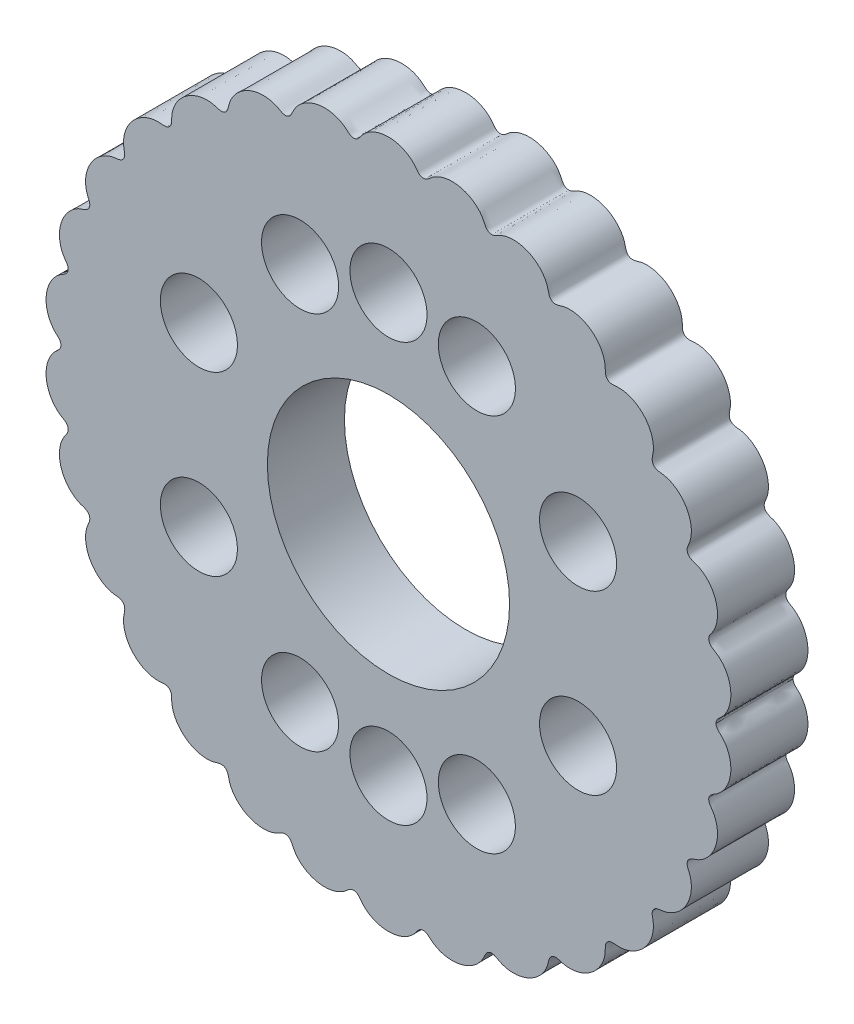
SolidWorks part; units mm, degrees
ref_plane "Plan de face" through (0, 0, 0) normal (0, 0, 1) x (1, 0, 0)
ref_plane "Plan de dessus" through (0, 0, 0) normal (0, 1, 0) x (1, 0, 0)
ref_plane "Plan de droite" through (0, 0, 0) normal (1, 0, 0) x (0, 0, -1)
sketch "Esquisse1" plane through (0, 0, 0) normal (0, 0, 1) x (1, 0, 0)
  line L0 (-1000, 0) -> (49000, 0) construction
  spline S0 degree 4 poles (29.8631, 8.2305) (29.8499, 8.1217) (29.8133, 7.9053) (29.7416, 7.64) (29.6157, 7.3353) (29.4839, 7.095) (29.3642, 6.911) (29.2467, 6.7537) (29.1538, 6.6056) (29.0902, 6.432) (29.0737, 6.2397) (29.1354, 6.023) (29.2904, 5.838) (29.4774, 5.7198) (29.6579, 5.6163) (29.8231, 5.5082) (30.0196, 5.3594) (30.2372, 5.1583) (30.5232, 4.8242) (30.8216, 4.3213) (31.0469, 3.679) (31.1337, 2.9091) (31.0567, 2.2277) (30.8902, 1.7108) (30.7109, 1.353) (30.5728, 1.1334) (30.4496, 0.9663) (30.3139, 0.8094) (30.1671, 0.6626) (30.0393, 0.549) (29.9425, 0.4546) (29.8803, 0.3777) (29.8449, 0.3262) (29.8141, 0.2716) (29.7888, 0.2141) (29.7717, 0.1632) (29.761, 0.1169) (29.7536, 0.0672) (29.7495, 0.017) (29.7494, -0.0206) (29.7556, -0.0898) (29.7678, -0.1499) (29.7904, -0.2203) (29.8284, -0.303) (29.8828, -0.3847) (29.9529, -0.4642) (30.04, -0.5488) (30.1416, -0.6407) (30.2572, -0.7512) (30.3813, -0.8854) (30.4962, -1.0277) (30.6276, -1.2147) (30.7721, -1.4641) (30.9126, -1.7829) (31.0276, -2.1744) (31.0935, -2.591) (31.107, -3.0187) (31.0662, -3.4508) (30.9693, -3.8803) (30.8145, -4.2991) (30.6117, -4.6792) (30.3965, -4.9766) (30.1917, -5.1998) (30.0146, -5.3603) (29.8643, -5.4786) (29.7061, -5.5858) (29.542, -5.684) (29.3671, -5.785) (29.2042, -5.9269) (29.0936, -6.1295) (29.0703, -6.371) (29.1391, -6.5914) (29.2598, -6.7697) (29.3791, -6.934) (29.4834, -7.0955) (29.5997, -7.3056) (29.715, -7.5703) (29.8147, -7.8969) (29.8798, -8.2857) (29.896, -8.684) (29.8631, -9.0858) (29.7829, -9.4799) (29.6574, -9.8612) (29.4885, -10.2243) (29.2783, -10.5643) (29.0303, -10.8742) (28.7824, -11.1148) (28.5506, -11.2952) (28.3468, -11.4258) (28.1768, -11.5188) (28.0006, -11.599) (27.8193, -11.6676) (27.6244, -11.7296) (27.4217, -11.8089) (27.242, -11.9571) (27.1301, -12.1734) (27.113, -12.404) (27.1707, -12.6114) (27.2542, -12.795) (27.3276, -12.9715) (27.3906, -13.1518) (27.4404, -13.3363) (27.4866, -13.5706) (27.5177, -13.8717) (27.5133, -14.2384) (27.4499, -14.6642) (27.3252, -15.0926) (27.1465, -15.4978) (26.919, -15.8739) (26.6474, -16.2153) (26.3365, -16.5168) (26.0024, -16.764) (25.654, -16.9563) (25.3418, -17.0779) (25.0791, -17.148) (24.8562, -17.1866) (24.6765, -17.2082) (24.4854, -17.2287) (24.2872, -17.2853) (24.1038, -17.4139) (23.9758, -17.6159) (23.9376, -17.8434) (23.9703, -18.0586) (24.0141, -18.2584) (24.0453, -18.4498) (24.0639, -18.6424) (24.0684, -18.8361) (24.0572, -19.0779) (24.0169, -19.3689) (23.9324, -19.7039) (23.7881, -20.0736) (23.5988, -20.4256) (23.3687, -20.7534) (23.1013, -21.0528) (22.8001, -21.3193) (22.4685, -21.5487) (22.1155, -21.7338) (21.7463, -21.8718) (21.4135, -21.9488) (21.1267, -21.9813) (20.8866, -21.9856) (20.6945, -21.9761) (20.4927, -21.9549) (20.2778, -21.9395) (20.0526, -21.9901) (19.8551, -22.131) (19.7349, -22.3281) (19.6935, -22.5401) (19.6935, -22.7421) (19.6905, -22.9333) (19.6768, -23.124) (19.6495, -23.3133) (19.599, -23.5469) (19.5081, -23.8358) (19.3582, -24.1709) (19.1304, -24.5365) (18.8451, -24.88) (18.5216, -25.1787) (18.1677, -25.4301) (17.7906, -25.6322) (17.3968, -25.7835) (17.0003, -25.8796) (16.6085, -25.9224) (16.2742, -25.9148) (16.002, -25.8785) (15.7793, -25.8278) (15.6036, -25.7769) (15.4169, -25.7147) (15.2087, -25.6689) (14.9779, -25.6954) (14.7639, -25.8189) (14.6256, -26.0056) (14.5611, -26.2088) (14.5217, -26.4015) (14.4779, -26.5791) (14.4104, -26.7974) (14.3058, -27.0513) (14.1452, -27.3445) (13.9122, -27.6625) (13.6308, -27.9579) (13.3029, -28.2232) (12.9393, -28.4488) (12.5446, -28.6295) (12.1242, -28.7604) (11.6841, -28.8357) (11.2535, -28.8501) (10.8884, -28.8124) (10.5927, -28.7466) (10.3651, -28.6736) (10.1875, -28.6026) (10.0156, -28.5191) (9.8485, -28.4261) (9.6736, -28.3252) (9.4693, -28.255) (9.2385, -28.2605) (9.0177, -28.3611) (8.8612, -28.5309) (8.7671, -28.7246) (8.6846, -28.91) (8.5968, -29.0812) (8.473, -29.2869) (8.3014, -29.519) (8.0684, -29.7687) (7.7643, -30.0195) (7.4274, -30.2327) (7.0631, -30.4051) (6.6816, -30.5327) (6.2887, -30.6146) (5.8897, -30.6499) (5.4902, -30.6379) (5.0979, -30.5781) (4.7655, -30.4837) (4.4934, -30.3731) (4.2784, -30.2619) (4.1128, -30.1612) (3.9553, -30.0487) (3.8052, -29.926) (3.6541, -29.7882) (3.484, -29.6523) (3.2679, -29.5716) (3.029, -29.5815) (2.8259, -29.676) (2.6778, -29.8193) (2.5645, -29.9746) (2.456, -30.1194) (2.311, -30.2931) (2.119, -30.4856) (1.8576, -30.6952) (1.5168, -30.9007) (1.1357, -31.0665) (0.7192, -31.185) (0.2877, -31.2495) (-0.1517, -31.2585) (-0.592, -31.2106) (-1.0254, -31.1045) (-1.4258, -30.9464) (-1.7456, -30.7669) (-1.9908, -30.5894) (-2.1706, -30.4322) (-2.3055, -30.2968) (-2.4301, -30.1521) (-2.5463, -30.0003) (-2.6635, -29.8363) (-2.8143, -29.6826) (-3.0226, -29.582) (-3.2659, -29.5708) (-3.484, -29.6523) (-3.654, -29.7882) (-3.8052, -29.926) (-3.9553, -30.0487) (-4.1128, -30.1612) (-4.2784, -30.2619) (-4.4934, -30.3731) (-4.7655, -30.4837) (-5.0979, -30.5781) (-5.4902, -30.6379) (-5.8897, -30.6499) (-6.2887, -30.6146) (-6.6816, -30.5327) (-7.0631, -30.4051) (-7.4274, -30.2327) (-7.7643, -30.0195) (-8.0684, -29.7687) (-8.3014, -29.519) (-8.473, -29.2869) (-8.5968, -29.0812) (-8.6846, -28.91) (-8.7671, -28.7246) (-8.8612, -28.5309) (-9.0177, -28.3611) (-9.2385, -28.2605) (-9.4693, -28.255) (-9.6736, -28.3252) (-9.8485, -28.4261) (-10.0156, -28.5191) (-10.1875, -28.6026) (-10.3651, -28.6736) (-10.5927, -28.7466) (-10.8884, -28.8124) (-11.2535, -28.8501) (-11.6841, -28.8357) (-12.1242, -28.7604) (-12.5446, -28.6295) (-12.9393, -28.4488) (-13.3029, -28.2232) (-13.6308, -27.9579) (-13.9122, -27.6625) (-14.1452, -27.3445) (-14.3058, -27.0513) (-14.4104, -26.7974) (-14.4779, -26.5791) (-14.5217, -26.4015) (-14.5611, -26.2088) (-14.6256, -26.0056) (-14.7639, -25.8189) (-14.9779, -25.6954) (-15.2087, -25.6689) (-15.4169, -25.7147) (-15.6036, -25.7769) (-15.7793, -25.8278) (-16.002, -25.8785) (-16.2742, -25.9148) (-16.6085, -25.9224) (-17.0003, -25.8796) (-17.3968, -25.7835) (-17.7906, -25.6322) (-18.1677, -25.4301) (-18.5216, -25.1787) (-18.8451, -24.88) (-19.1304, -24.5365) (-19.3582, -24.1709) (-19.5081, -23.8358) (-19.599, -23.5469) (-19.6495, -23.3133) (-19.6768, -23.124) (-19.6905, -22.9333) (-19.6935, -22.7421) (-19.6935, -22.5401) (-19.7349, -22.3281) (-19.8551, -22.131) (-20.0526, -21.9901) (-20.2778, -21.9395) (-20.4927, -21.9549) (-20.6945, -21.9761) (-20.8866, -21.9856) (-21.1267, -21.9813) (-21.4135, -21.9488) (-21.7463, -21.8718) (-22.1155, -21.7338) (-22.4685, -21.5487) (-22.8001, -21.3193) (-23.1013, -21.0528) (-23.3687, -20.7534) (-23.5988, -20.4256) (-23.7881, -20.0736) (-23.9324, -19.7039) (-24.0169, -19.3689) (-24.0572, -19.0779) (-24.0684, -18.8361) (-24.0639, -18.6424) (-24.0453, -18.4498) (-24.0141, -18.2584) (-23.9703, -18.0586) (-23.9376, -17.8434) (-23.9758, -17.6159) (-24.1038, -17.4139) (-24.2872, -17.2853) (-24.4854, -17.2287) (-24.6765, -17.2082) (-24.8562, -17.1866) (-25.0791, -17.148) (-25.3418, -17.0779) (-25.654, -16.9563) (-26.0024, -16.764) (-26.3365, -16.5168) (-26.6474, -16.2153) (-26.919, -15.8739) (-27.1465, -15.4978) (-27.3252, -15.0926) (-27.4499, -14.6642) (-27.5133, -14.2384) (-27.5177, -13.8717) (-27.4866, -13.5706) (-27.4404, -13.3363) (-27.3906, -13.1518) (-27.3276, -12.9715) (-27.2542, -12.795) (-27.1707, -12.6114) (-27.113, -12.404) (-27.1301, -12.1734) (-27.242, -11.9571) (-27.4217, -11.8089) (-27.6244, -11.7296) (-27.8193, -11.6676) (-28.0006, -11.599) (-28.1768, -11.5188) (-28.3468, -11.4258) (-28.5506, -11.2952) (-28.7824, -11.1148) (-29.0303, -10.8742) (-29.2783, -10.5643) (-29.4885, -10.2243) (-29.6574, -9.8612) (-29.7829, -9.4799) (-29.8631, -9.0858) (-29.896, -8.684) (-29.8798, -8.2857) (-29.8147, -7.8969) (-29.715, -7.5703) (-29.5997, -7.3056) (-29.4834, -7.0955) (-29.3791, -6.934) (-29.2598, -6.7697) (-29.1391, -6.5914) (-29.0703, -6.371) (-29.0936, -6.1295) (-29.2042, -5.9269) (-29.3671, -5.785) (-29.542, -5.684) (-29.7061, -5.5858) (-29.8643, -5.4786) (-30.0146, -5.3603) (-30.1917, -5.1998) (-30.3965, -4.9766) (-30.6117, -4.6792) (-30.8145, -4.2991) (-30.9693, -3.8803) (-31.0662, -3.4508) (-31.107, -3.0187) (-31.0935, -2.591) (-31.0276, -2.1744) (-30.9126, -1.7829) (-30.7537, -1.4222) (-30.58, -1.1364) (-30.4124, -0.919) (-30.2572, -0.7512) (-30.1416, -0.6407) (-30.04, -0.5488) (-29.9529, -0.4642) (-29.8828, -0.3847) (-29.8284, -0.303) (-29.7904, -0.2203) (-29.7678, -0.1499) (-29.7556, -0.0898) (-29.7494, -0.0206) (-29.7495, 0.0226) (-29.7561, 0.094) (-29.7693, 0.1557) (-29.7888, 0.2141) (-29.8141, 0.2716) (-29.8449, 0.3262) (-29.8803, 0.3778) (-29.9262, 0.4344) (-29.9834, 0.4947) (-30.0703, 0.5765) (-30.1854, 0.6811) (-30.3139, 0.8093) (-30.4835, 1.0056) (-30.6621, 1.2611) (-30.8291, 1.576) (-30.9678, 1.9517) (-31.0574, 2.3341) (-31.1011, 2.7166) (-31.1012, 3.1978) (-31.0148, 3.7704) (-30.8216, 4.3213) (-30.5232, 4.8242) (-30.2372, 5.1583) (-30.0196, 5.3594) (-29.8231, 5.5082) (-29.6579, 5.6163) (-29.4774, 5.7198) (-29.2904, 5.838) (-29.1354, 6.023) (-29.0737, 6.2397) (-29.0902, 6.432) (-29.1538, 6.6056) (-29.2467, 6.7537) (-29.3642, 6.911) (-29.4839, 7.095) (-29.6157, 7.3353) (-29.7416, 7.64) (-29.8133, 7.9053) (-29.8499, 8.1217) (-29.8631, 8.2305) knots 0 0 0 0 0 0.003392 0.006784 0.00848 0.010176 0.011872 0.013568 0.014566 0.015563 0.017559 0.01944 0.02132 0.022846 0.024371 0.025896 0.027421 0.030471 0.033522 0.039468 0.045414 0.051361 0.057307 0.060517 0.062121 0.063726 0.065331 0.066935 0.06854 0.070145 0.070628 0.071112 0.071596 0.07208 0.072564 0.073048 0.073289 0.073531 0.074015 0.07448 0.074945 0.07541 0.075875 0.076805 0.077735 0.078442 0.079149 0.080563 0.081977 0.083391 0.084805 0.086218 0.089046 0.092302 0.095557 0.098813 0.102069 0.105514 0.10896 0.112405 0.115851 0.118808 0.120287 0.121766 0.123244 0.124723 0.126202 0.12768 0.1295 0.131319 0.133154 0.134989 0.136475 0.137961 0.139448 0.140934 0.143906 0.146878 0.14999 0.153103 0.156215 0.159327 0.162414 0.1655 0.168586 0.171672 0.174668 0.176165 0.177663 0.179161 0.180659 0.182156 0.183654 0.185506 0.187357 0.189175 0.190994 0.192471 0.193949 0.195426 0.196904 0.198382 0.199859 0.202814 0.206257 0.2097 0.213143 0.216586 0.219928 0.22327 0.226613 0.229955 0.232755 0.235555 0.236955 0.238355 0.239755 0.241155 0.242909 0.244663 0.246515 0.248366 0.249864 0.251362 0.252859 0.254357 0.255855 0.257353 0.260348 0.263434 0.266521 0.269607 0.272693 0.275805 0.278918 0.28203 0.285143 0.288115 0.291087 0.292573 0.294059 0.295545 0.297031 0.298866 0.300701 0.302521 0.30434 0.305819 0.307297 0.308776 0.310255 0.311733 0.313212 0.31617 0.319615 0.323061 0.326506 0.329952 0.333207 0.336463 0.339719 0.342974 0.345802 0.34863 0.350043 0.351457 0.352871 0.354285 0.356145 0.358005 0.359865 0.361725 0.363139 0.364553 0.365967 0.367381 0.370208 0.373036 0.376292 0.379547 0.382803 0.386059 0.389504 0.39295 0.396395 0.399841 0.402798 0.404277 0.405755 0.407234 0.408713 0.410191 0.41167 0.41349 0.415309 0.417144 0.418979 0.420465 0.421951 0.423437 0.424923 0.427896 0.430868 0.43398 0.437092 0.440205 0.443317 0.446403 0.44949 0.452576 0.455662 0.458657 0.460155 0.461653 0.463151 0.464649 0.466146 0.467644 0.469495 0.471347 0.473101 0.474856 0.476256 0.477656 0.479056 0.480456 0.483256 0.486055 0.489398 0.49274 0.496082 0.499424 0.502867 0.50631 0.509753 0.513196 0.516151 0.517629 0.519106 0.520584 0.522061 0.523539 0.525016 0.526835 0.528653 0.530505 0.532356 0.533854 0.535351 0.536849 0.538347 0.539845 0.541343 0.544338 0.547424 0.55051 0.553597 0.556683 0.559795 0.562908 0.56602 0.569132 0.572104 0.575077 0.576563 0.578049 0.579535 0.581021 0.582856 0.584691 0.58651 0.58833 0.589809 0.591287 0.592766 0.594245 0.595723 0.597202 0.600159 0.603605 0.60705 0.610496 0.613941 0.617197 0.620453 0.623708 0.626964 0.629792 0.632619 0.634033 0.635447 0.636861 0.638275 0.640135 0.641995 0.643855 0.645715 0.647129 0.648543 0.649957 0.65137 0.654198 0.657026 0.660281 0.663537 0.666793 0.670048 0.673494 0.676939 0.680385 0.68383 0.686788 0.688267 0.689745 0.691224 0.692703 0.694181 0.69566 0.697479 0.699299 0.701134 0.702969 0.704455 0.705941 0.707427 0.708913 0.711885 0.714857 0.71797 0.721082 0.724195 0.727307 0.730393 0.733479 0.736566 0.739652 0.742647 0.744145 0.745643 0.747141 0.748638 0.750136 0.751634 0.753485 0.755337 0.757091 0.758845 0.760245 0.761645 0.763045 0.764445 0.767245 0.770045 0.773387 0.77673 0.780072 0.783414 0.786857 0.7903 0.793743 0.797186 0.800141 0.801618 0.803096 0.804574 0.806051 0.807529 0.809006 0.810825 0.812643 0.814494 0.816346 0.817844 0.819341 0.820839 0.822337 0.823835 0.825332 0.828328 0.831414 0.8345 0.837586 0.840673 0.843785 0.846897 0.85001 0.853122 0.856094 0.859066 0.860552 0.862039 0.863525 0.865011 0.866846 0.868681 0.8705 0.87232 0.873798 0.875277 0.876756 0.878234 0.879713 0.881192 0.884149 0.887595 0.89104 0.894486 0.897931 0.901187 0.904443 0.907698 0.910954 0.913782 0.916609 0.918023 0.919437 0.920851 0.921558 0.922265 0.923195 0.924125 0.92459 0.925055 0.92552 0.925985 0.926469 0.926952 0.927436 0.92792 0.928404 0.928888 0.929372 0.929855 0.930658 0.93146 0.933065 0.934669 0.936274 0.939483 0.942693 0.945666 0.948639 0.951612 0.954586 0.960532 0.966478 0.969529 0.972579 0.974104 0.975629 0.977154 0.97868 0.98056 0.982441 0.984437 0.985434 0.986432 0.988128 0.989824 0.99152 0.993216 0.996608 1 1 1 1 1 construction
  spline S1 degree 4 poles (29.75, 0) (29.75, -0.0128) (29.751, -0.0384) (29.7556, -0.0898) (29.7678, -0.1499) (29.7904, -0.2203) (29.8284, -0.303) (29.8828, -0.3847) (29.9529, -0.4642) (30.04, -0.5488) (30.1416, -0.6407) (30.2572, -0.7512) (30.3813, -0.8854) (30.4962, -1.0277) (30.6276, -1.2147) (30.7721, -1.4641) (30.9126, -1.7829) (31.0276, -2.1744) (31.0935, -2.591) (31.107, -3.0187) (31.0662, -3.4508) (30.9693, -3.8803) (30.8145, -4.2991) (30.6117, -4.6792) (30.3965, -4.9766) (30.1917, -5.1998) (30.0146, -5.3603) (29.8643, -5.4786) (29.7061, -5.5858) (29.542, -5.684) (29.3671, -5.785) (29.2042, -5.9269) (29.0936, -6.1295) (29.0703, -6.371) (29.1391, -6.5914) (29.2598, -6.7697) (29.3791, -6.934) (29.4834, -7.0955) (29.5997, -7.3056) (29.715, -7.5703) (29.8147, -7.8969) (29.8798, -8.2857) (29.896, -8.684) (29.8631, -9.0858) (29.7829, -9.4799) (29.6574, -9.8612) (29.4885, -10.2243) (29.2783, -10.5643) (29.0303, -10.8742) (28.7824, -11.1148) (28.5506, -11.2952) (28.3468, -11.4258) (28.1768, -11.5188) (28.0006, -11.599) (27.8193, -11.6676) (27.6244, -11.7296) (27.4217, -11.8089) (27.242, -11.9571) (27.1301, -12.1734) (27.113, -12.404) (27.1707, -12.6114) (27.2542, -12.795) (27.3276, -12.9715) (27.3906, -13.1518) (27.4404, -13.3363) (27.4866, -13.5706) (27.5177, -13.8717) (27.5133, -14.2384) (27.4499, -14.6642) (27.3252, -15.0926) (27.1465, -15.4978) (26.919, -15.8739) (26.6474, -16.2153) (26.3365, -16.5168) (26.0024, -16.764) (25.654, -16.9563) (25.3418, -17.0779) (25.0791, -17.148) (24.8562, -17.1866) (24.6765, -17.2082) (24.4854, -17.2287) (24.2872, -17.2853) (24.1038, -17.4139) (23.9758, -17.6159) (23.9376, -17.8434) (23.9703, -18.0586) (24.0141, -18.2584) (24.0453, -18.4498) (24.0639, -18.6424) (24.0684, -18.8361) (24.0572, -19.0779) (24.0169, -19.3689) (23.9324, -19.7039) (23.7881, -20.0736) (23.5988, -20.4256) (23.3687, -20.7534) (23.1013, -21.0528) (22.8001, -21.3193) (22.4685, -21.5487) (22.1155, -21.7338) (21.7463, -21.8718) (21.4135, -21.9488) (21.1267, -21.9813) (20.8866, -21.9856) (20.6945, -21.9761) (20.4927, -21.9549) (20.2778, -21.9395) (20.0526, -21.9901) (19.8551, -22.131) (19.7349, -22.3281) (19.6935, -22.5401) (19.6935, -22.7421) (19.6905, -22.9333) (19.6768, -23.124) (19.6495, -23.3133) (19.599, -23.5469) (19.5081, -23.8358) (19.3582, -24.1709) (19.1304, -24.5365) (18.8451, -24.88) (18.5216, -25.1787) (18.1677, -25.4301) (17.7906, -25.6322) (17.3968, -25.7835) (17.0003, -25.8796) (16.6085, -25.9224) (16.2742, -25.9148) (16.002, -25.8785) (15.7793, -25.8278) (15.6036, -25.7769) (15.4169, -25.7147) (15.2087, -25.6689) (14.9779, -25.6954) (14.7639, -25.8189) (14.6256, -26.0056) (14.5611, -26.2088) (14.5217, -26.4015) (14.4779, -26.5791) (14.4104, -26.7974) (14.3058, -27.0513) (14.1452, -27.3445) (13.9122, -27.6625) (13.6308, -27.9579) (13.3029, -28.2232) (12.9393, -28.4488) (12.5446, -28.6295) (12.1242, -28.7604) (11.6841, -28.8357) (11.2535, -28.8501) (10.8884, -28.8124) (10.5927, -28.7466) (10.3651, -28.6736) (10.1875, -28.6026) (10.0156, -28.5191) (9.8485, -28.4261) (9.6736, -28.3252) (9.4693, -28.255) (9.2385, -28.2605) (9.0177, -28.3611) (8.8612, -28.5309) (8.7671, -28.7246) (8.6846, -28.91) (8.5968, -29.0812) (8.473, -29.2869) (8.3014, -29.519) (8.0684, -29.7687) (7.7643, -30.0195) (7.4274, -30.2327) (7.0631, -30.4051) (6.6816, -30.5327) (6.2887, -30.6146) (5.8897, -30.6499) (5.4902, -30.6379) (5.0979, -30.5781) (4.7655, -30.4837) (4.4934, -30.3731) (4.2784, -30.2619) (4.1128, -30.1612) (3.9553, -30.0487) (3.8052, -29.926) (3.6541, -29.7882) (3.484, -29.6523) (3.2679, -29.5716) (3.029, -29.5815) (2.8259, -29.676) (2.6778, -29.8193) (2.5645, -29.9746) (2.456, -30.1194) (2.311, -30.2931) (2.119, -30.4856) (1.8576, -30.6952) (1.5168, -30.9007) (1.1357, -31.0665) (0.7192, -31.185) (0.2877, -31.2495) (-0.1517, -31.2585) (-0.592, -31.2106) (-1.0254, -31.1045) (-1.4258, -30.9464) (-1.7456, -30.7669) (-1.9908, -30.5894) (-2.1706, -30.4322) (-2.3055, -30.2968) (-2.4301, -30.1521) (-2.5463, -30.0003) (-2.6635, -29.8363) (-2.8143, -29.6826) (-3.0226, -29.582) (-3.2659, -29.5708) (-3.484, -29.6523) (-3.654, -29.7882) (-3.8052, -29.926) (-3.9553, -30.0487) (-4.1128, -30.1612) (-4.2784, -30.2619) (-4.4934, -30.3731) (-4.7655, -30.4837) (-5.0979, -30.5781) (-5.4902, -30.6379) (-5.8897, -30.6499) (-6.2887, -30.6146) (-6.6816, -30.5327) (-7.0631, -30.4051) (-7.4274, -30.2327) (-7.7643, -30.0195) (-8.0684, -29.7687) (-8.3014, -29.519) (-8.473, -29.2869) (-8.5968, -29.0812) (-8.6846, -28.91) (-8.7671, -28.7246) (-8.8612, -28.5309) (-9.0177, -28.3611) (-9.2385, -28.2605) (-9.4693, -28.255) (-9.6736, -28.3252) (-9.8485, -28.4261) (-10.0156, -28.5191) (-10.1875, -28.6026) (-10.3651, -28.6736) (-10.5927, -28.7466) (-10.8884, -28.8124) (-11.2535, -28.8501) (-11.6841, -28.8357) (-12.1242, -28.7604) (-12.5446, -28.6295) (-12.9393, -28.4488) (-13.3029, -28.2232) (-13.6308, -27.9579) (-13.9122, -27.6625) (-14.1452, -27.3445) (-14.3058, -27.0513) (-14.4104, -26.7974) (-14.4779, -26.5791) (-14.5217, -26.4015) (-14.5611, -26.2088) (-14.6256, -26.0056) (-14.7639, -25.8189) (-14.9779, -25.6954) (-15.2087, -25.6689) (-15.4169, -25.7147) (-15.6036, -25.7769) (-15.7793, -25.8278) (-16.002, -25.8785) (-16.2742, -25.9148) (-16.6085, -25.9224) (-17.0003, -25.8796) (-17.3968, -25.7835) (-17.7906, -25.6322) (-18.1677, -25.4301) (-18.5216, -25.1787) (-18.8451, -24.88) (-19.1304, -24.5365) (-19.3582, -24.1709) (-19.5081, -23.8358) (-19.599, -23.5469) (-19.6495, -23.3133) (-19.6768, -23.124) (-19.6905, -22.9333) (-19.6935, -22.7421) (-19.6935, -22.5401) (-19.7349, -22.3281) (-19.8551, -22.131) (-20.0526, -21.9901) (-20.2778, -21.9395) (-20.4927, -21.9549) (-20.6945, -21.9761) (-20.8866, -21.9856) (-21.1267, -21.9813) (-21.4135, -21.9488) (-21.7463, -21.8718) (-22.1155, -21.7338) (-22.4685, -21.5487) (-22.8001, -21.3193) (-23.1013, -21.0528) (-23.3687, -20.7534) (-23.5988, -20.4256) (-23.7881, -20.0736) (-23.9324, -19.7039) (-24.0169, -19.3689) (-24.0572, -19.0779) (-24.0684, -18.8361) (-24.0639, -18.6424) (-24.0453, -18.4498) (-24.0141, -18.2584) (-23.9703, -18.0586) (-23.9376, -17.8434) (-23.9758, -17.6159) (-24.1038, -17.4139) (-24.2872, -17.2853) (-24.4854, -17.2287) (-24.6765, -17.2082) (-24.8562, -17.1866) (-25.0791, -17.148) (-25.3418, -17.0779) (-25.654, -16.9563) (-26.0024, -16.764) (-26.3365, -16.5168) (-26.6474, -16.2153) (-26.919, -15.8739) (-27.1465, -15.4978) (-27.3252, -15.0926) (-27.4499, -14.6642) (-27.5133, -14.2384) (-27.5177, -13.8717) (-27.4866, -13.5706) (-27.4404, -13.3363) (-27.3906, -13.1518) (-27.3276, -12.9715) (-27.2542, -12.795) (-27.1707, -12.6114) (-27.113, -12.404) (-27.1301, -12.1734) (-27.242, -11.9571) (-27.4217, -11.8089) (-27.6244, -11.7296) (-27.8193, -11.6676) (-28.0006, -11.599) (-28.1768, -11.5188) (-28.3468, -11.4258) (-28.5506, -11.2952) (-28.7824, -11.1148) (-29.0303, -10.8742) (-29.2783, -10.5643) (-29.4885, -10.2243) (-29.6574, -9.8612) (-29.7829, -9.4799) (-29.8631, -9.0858) (-29.896, -8.684) (-29.8798, -8.2857) (-29.8147, -7.8969) (-29.715, -7.5703) (-29.5997, -7.3056) (-29.4834, -7.0955) (-29.3791, -6.934) (-29.2598, -6.7697) (-29.1391, -6.5914) (-29.0703, -6.371) (-29.0936, -6.1295) (-29.2042, -5.9269) (-29.3671, -5.785) (-29.542, -5.684) (-29.7061, -5.5858) (-29.8643, -5.4786) (-30.0146, -5.3603) (-30.1917, -5.1998) (-30.3965, -4.9766) (-30.6117, -4.6792) (-30.8145, -4.2991) (-30.9693, -3.8803) (-31.0662, -3.4508) (-31.107, -3.0187) (-31.0935, -2.591) (-31.0276, -2.1744) (-30.9126, -1.7829) (-30.7537, -1.4222) (-30.58, -1.1364) (-30.4124, -0.919) (-30.2572, -0.7512) (-30.1416, -0.6407) (-30.04, -0.5488) (-29.9529, -0.4642) (-29.8828, -0.3847) (-29.8284, -0.303) (-29.7904, -0.2203) (-29.7678, -0.1499) (-29.7556, -0.0898) (-29.751, -0.0384) (-29.75, -0.0128) (-29.75, 0) knots 0.074015 0.074015 0.074015 0.074015 0.074015 0.07448 0.074945 0.07541 0.075875 0.076805 0.077735 0.078442 0.079149 0.080563 0.081977 0.083391 0.084805 0.086218 0.089046 0.092302 0.095557 0.098813 0.102069 0.105514 0.10896 0.112405 0.115851 0.118808 0.120287 0.121766 0.123244 0.124723 0.126202 0.12768 0.1295 0.131319 0.133154 0.134989 0.136475 0.137961 0.139448 0.140934 0.143906 0.146878 0.14999 0.153103 0.156215 0.159327 0.162414 0.1655 0.168586 0.171672 0.174668 0.176165 0.177663 0.179161 0.180659 0.182156 0.183654 0.185506 0.187357 0.189175 0.190994 0.192471 0.193949 0.195426 0.196904 0.198382 0.199859 0.202814 0.206257 0.2097 0.213143 0.216586 0.219928 0.22327 0.226613 0.229955 0.232755 0.235555 0.236955 0.238355 0.239755 0.241155 0.242909 0.244663 0.246515 0.248366 0.249864 0.251362 0.252859 0.254357 0.255855 0.257353 0.260348 0.263434 0.266521 0.269607 0.272693 0.275805 0.278918 0.28203 0.285143 0.288115 0.291087 0.292573 0.294059 0.295545 0.297031 0.298866 0.300701 0.302521 0.30434 0.305819 0.307297 0.308776 0.310255 0.311733 0.313212 0.31617 0.319615 0.323061 0.326506 0.329952 0.333207 0.336463 0.339719 0.342974 0.345802 0.34863 0.350043 0.351457 0.352871 0.354285 0.356145 0.358005 0.359865 0.361725 0.363139 0.364553 0.365967 0.367381 0.370208 0.373036 0.376292 0.379547 0.382803 0.386059 0.389504 0.39295 0.396395 0.399841 0.402798 0.404277 0.405755 0.407234 0.408713 0.410191 0.41167 0.41349 0.415309 0.417144 0.418979 0.420465 0.421951 0.423437 0.424923 0.427896 0.430868 0.43398 0.437092 0.440205 0.443317 0.446403 0.44949 0.452576 0.455662 0.458657 0.460155 0.461653 0.463151 0.464649 0.466146 0.467644 0.469495 0.471347 0.473101 0.474856 0.476256 0.477656 0.479056 0.480456 0.483256 0.486055 0.489398 0.49274 0.496082 0.499424 0.502867 0.50631 0.509753 0.513196 0.516151 0.517629 0.519106 0.520584 0.522061 0.523539 0.525016 0.526835 0.528653 0.530505 0.532356 0.533854 0.535351 0.536849 0.538347 0.539845 0.541343 0.544338 0.547424 0.55051 0.553597 0.556683 0.559795 0.562908 0.56602 0.569132 0.572104 0.575077 0.576563 0.578049 0.579535 0.581021 0.582856 0.584691 0.58651 0.58833 0.589809 0.591287 0.592766 0.594245 0.595723 0.597202 0.600159 0.603605 0.60705 0.610496 0.613941 0.617197 0.620453 0.623708 0.626964 0.629792 0.632619 0.634033 0.635447 0.636861 0.638275 0.640135 0.641995 0.643855 0.645715 0.647129 0.648543 0.649957 0.65137 0.654198 0.657026 0.660281 0.663537 0.666793 0.670048 0.673494 0.676939 0.680385 0.68383 0.686788 0.688267 0.689745 0.691224 0.692703 0.694181 0.69566 0.697479 0.699299 0.701134 0.702969 0.704455 0.705941 0.707427 0.708913 0.711885 0.714857 0.71797 0.721082 0.724195 0.727307 0.730393 0.733479 0.736566 0.739652 0.742647 0.744145 0.745643 0.747141 0.748638 0.750136 0.751634 0.753485 0.755337 0.757091 0.758845 0.760245 0.761645 0.763045 0.764445 0.767245 0.770045 0.773387 0.77673 0.780072 0.783414 0.786857 0.7903 0.793743 0.797186 0.800141 0.801618 0.803096 0.804574 0.806051 0.807529 0.809006 0.810825 0.812643 0.814494 0.816346 0.817844 0.819341 0.820839 0.822337 0.823835 0.825332 0.828328 0.831414 0.8345 0.837586 0.840673 0.843785 0.846897 0.85001 0.853122 0.856094 0.859066 0.860552 0.862039 0.863525 0.865011 0.866846 0.868681 0.8705 0.87232 0.873798 0.875277 0.876756 0.878234 0.879713 0.881192 0.884149 0.887595 0.89104 0.894486 0.897931 0.901187 0.904443 0.907698 0.910954 0.913782 0.916609 0.918023 0.919437 0.920851 0.921558 0.922265 0.923195 0.924125 0.92459 0.925055 0.92552 0.925985 0.925985 0.925985 0.925985 0.925985 construction
  spline S2 degree 4 poles (29.75, 0) (29.75, 0.0128) (29.751, 0.0384) (29.7556, 0.0898) (29.7678, 0.1499) (29.7904, 0.2203) (29.8284, 0.303) (29.8828, 0.3847) (29.9529, 0.4642) (30.04, 0.5488) (30.1416, 0.6407) (30.2572, 0.7512) (30.3813, 0.8854) (30.4962, 1.0277) (30.6276, 1.2147) (30.7721, 1.4641) (30.9126, 1.7829) (31.0276, 2.1744) (31.0935, 2.591) (31.107, 3.0187) (31.0662, 3.4508) (30.9693, 3.8803) (30.8145, 4.2991) (30.6117, 4.6792) (30.3965, 4.9766) (30.1917, 5.1998) (30.0146, 5.3603) (29.8643, 5.4786) (29.7061, 5.5858) (29.542, 5.684) (29.3671, 5.785) (29.2042, 5.9269) (29.0936, 6.1295) (29.0703, 6.371) (29.1391, 6.5914) (29.2598, 6.7697) (29.3791, 6.934) (29.4834, 7.0955) (29.5997, 7.3056) (29.715, 7.5703) (29.8147, 7.8969) (29.8798, 8.2857) (29.896, 8.684) (29.8631, 9.0858) (29.7829, 9.4799) (29.6574, 9.8612) (29.4885, 10.2243) (29.2783, 10.5643) (29.0303, 10.8742) (28.7824, 11.1148) (28.5506, 11.2952) (28.3468, 11.4258) (28.1768, 11.5188) (28.0006, 11.599) (27.8193, 11.6676) (27.6244, 11.7296) (27.4217, 11.8089) (27.242, 11.9571) (27.1301, 12.1734) (27.113, 12.404) (27.1707, 12.6114) (27.2542, 12.795) (27.3276, 12.9715) (27.3906, 13.1518) (27.4404, 13.3363) (27.4866, 13.5706) (27.5177, 13.8717) (27.5133, 14.2384) (27.4499, 14.6642) (27.3252, 15.0926) (27.1465, 15.4978) (26.919, 15.8739) (26.6474, 16.2153) (26.3365, 16.5168) (26.0024, 16.764) (25.654, 16.9563) (25.3418, 17.0779) (25.0791, 17.148) (24.8562, 17.1866) (24.6765, 17.2082) (24.4854, 17.2287) (24.2872, 17.2853) (24.1038, 17.4139) (23.9758, 17.6159) (23.9376, 17.8434) (23.9703, 18.0586) (24.0141, 18.2584) (24.0453, 18.4498) (24.0639, 18.6424) (24.0684, 18.8361) (24.0572, 19.0779) (24.0169, 19.3689) (23.9324, 19.7039) (23.7881, 20.0736) (23.5988, 20.4256) (23.3687, 20.7534) (23.1013, 21.0528) (22.8001, 21.3193) (22.4685, 21.5487) (22.1155, 21.7338) (21.7463, 21.8718) (21.4135, 21.9488) (21.1267, 21.9813) (20.8866, 21.9856) (20.6945, 21.9761) (20.4927, 21.9549) (20.2778, 21.9395) (20.0526, 21.9901) (19.8551, 22.131) (19.7349, 22.3281) (19.6935, 22.5401) (19.6935, 22.7421) (19.6905, 22.9333) (19.6768, 23.124) (19.6495, 23.3133) (19.599, 23.5469) (19.5081, 23.8358) (19.3582, 24.1709) (19.1304, 24.5365) (18.8451, 24.88) (18.5216, 25.1787) (18.1677, 25.4301) (17.7906, 25.6322) (17.3968, 25.7835) (17.0003, 25.8796) (16.6085, 25.9224) (16.2742, 25.9148) (16.002, 25.8785) (15.7793, 25.8278) (15.6036, 25.7769) (15.4169, 25.7147) (15.2087, 25.6689) (14.9779, 25.6954) (14.7639, 25.8189) (14.6256, 26.0056) (14.5611, 26.2088) (14.5217, 26.4015) (14.4779, 26.5791) (14.4104, 26.7974) (14.3058, 27.0513) (14.1452, 27.3445) (13.9122, 27.6625) (13.6308, 27.9579) (13.3029, 28.2232) (12.9393, 28.4488) (12.5446, 28.6295) (12.1242, 28.7604) (11.6841, 28.8357) (11.2535, 28.8501) (10.8884, 28.8124) (10.5927, 28.7466) (10.3651, 28.6736) (10.1875, 28.6026) (10.0156, 28.5191) (9.8485, 28.4261) (9.6736, 28.3252) (9.4693, 28.255) (9.2385, 28.2605) (9.0177, 28.3611) (8.8612, 28.5309) (8.7671, 28.7246) (8.6846, 28.91) (8.5968, 29.0812) (8.473, 29.2869) (8.3014, 29.519) (8.0684, 29.7687) (7.7643, 30.0195) (7.4274, 30.2327) (7.0631, 30.4051) (6.6816, 30.5327) (6.2887, 30.6146) (5.8897, 30.6499) (5.4902, 30.6379) (5.0979, 30.5781) (4.7655, 30.4837) (4.4934, 30.3731) (4.2784, 30.2619) (4.1128, 30.1612) (3.9553, 30.0487) (3.8052, 29.926) (3.6541, 29.7882) (3.484, 29.6523) (3.2679, 29.5716) (3.029, 29.5815) (2.8259, 29.676) (2.6778, 29.8193) (2.5645, 29.9746) (2.456, 30.1194) (2.311, 30.2931) (2.119, 30.4856) (1.8576, 30.6952) (1.5168, 30.9007) (1.1357, 31.0665) (0.7192, 31.185) (0.2877, 31.2495) (-0.1517, 31.2585) (-0.592, 31.2106) (-1.0254, 31.1045) (-1.4258, 30.9464) (-1.7456, 30.7669) (-1.9908, 30.5894) (-2.1706, 30.4322) (-2.3055, 30.2968) (-2.4301, 30.1521) (-2.5463, 30.0003) (-2.6635, 29.8363) (-2.8143, 29.6826) (-3.0226, 29.582) (-3.2659, 29.5708) (-3.484, 29.6523) (-3.654, 29.7882) (-3.8052, 29.926) (-3.9553, 30.0487) (-4.1128, 30.1612) (-4.2784, 30.2619) (-4.4934, 30.3731) (-4.7655, 30.4837) (-5.0979, 30.5781) (-5.4902, 30.6379) (-5.8897, 30.6499) (-6.2887, 30.6146) (-6.6816, 30.5327) (-7.0631, 30.4051) (-7.4274, 30.2327) (-7.7643, 30.0195) (-8.0684, 29.7687) (-8.3014, 29.519) (-8.473, 29.2869) (-8.5968, 29.0812) (-8.6846, 28.91) (-8.7671, 28.7246) (-8.8612, 28.5309) (-9.0177, 28.3611) (-9.2385, 28.2605) (-9.4693, 28.255) (-9.6736, 28.3252) (-9.8485, 28.4261) (-10.0156, 28.5191) (-10.1875, 28.6026) (-10.3651, 28.6736) (-10.5927, 28.7466) (-10.8884, 28.8124) (-11.2535, 28.8501) (-11.6841, 28.8357) (-12.1242, 28.7604) (-12.5446, 28.6295) (-12.9393, 28.4488) (-13.3029, 28.2232) (-13.6308, 27.9579) (-13.9122, 27.6625) (-14.1452, 27.3445) (-14.3058, 27.0513) (-14.4104, 26.7974) (-14.4779, 26.5791) (-14.5217, 26.4015) (-14.5611, 26.2088) (-14.6256, 26.0056) (-14.7639, 25.8189) (-14.9779, 25.6954) (-15.2087, 25.6689) (-15.4169, 25.7147) (-15.6036, 25.7769) (-15.7793, 25.8278) (-16.002, 25.8785) (-16.2742, 25.9148) (-16.6085, 25.9224) (-17.0003, 25.8796) (-17.3968, 25.7835) (-17.7906, 25.6322) (-18.1677, 25.4301) (-18.5216, 25.1787) (-18.8451, 24.88) (-19.1304, 24.5365) (-19.3582, 24.1709) (-19.5081, 23.8358) (-19.599, 23.5469) (-19.6495, 23.3133) (-19.6768, 23.124) (-19.6905, 22.9333) (-19.6935, 22.7421) (-19.6935, 22.5401) (-19.7349, 22.3281) (-19.8551, 22.131) (-20.0526, 21.9901) (-20.2778, 21.9395) (-20.4927, 21.9549) (-20.6945, 21.9761) (-20.8866, 21.9856) (-21.1267, 21.9813) (-21.4135, 21.9488) (-21.7463, 21.8718) (-22.1155, 21.7338) (-22.4685, 21.5487) (-22.8001, 21.3193) (-23.1013, 21.0528) (-23.3687, 20.7534) (-23.5988, 20.4256) (-23.7881, 20.0736) (-23.9324, 19.7039) (-24.0169, 19.3689) (-24.0572, 19.0779) (-24.0684, 18.8361) (-24.0639, 18.6424) (-24.0453, 18.4498) (-24.0141, 18.2584) (-23.9703, 18.0586) (-23.9376, 17.8434) (-23.9758, 17.6159) (-24.1038, 17.4139) (-24.2872, 17.2853) (-24.4854, 17.2287) (-24.6765, 17.2082) (-24.8562, 17.1866) (-25.0791, 17.148) (-25.3418, 17.0779) (-25.654, 16.9563) (-26.0024, 16.764) (-26.3365, 16.5168) (-26.6474, 16.2153) (-26.919, 15.8739) (-27.1465, 15.4978) (-27.3252, 15.0926) (-27.4499, 14.6642) (-27.5133, 14.2384) (-27.5177, 13.8717) (-27.4866, 13.5706) (-27.4404, 13.3363) (-27.3906, 13.1518) (-27.3276, 12.9715) (-27.2542, 12.795) (-27.1707, 12.6114) (-27.113, 12.404) (-27.1301, 12.1734) (-27.242, 11.9571) (-27.4217, 11.8089) (-27.6244, 11.7296) (-27.8193, 11.6676) (-28.0006, 11.599) (-28.1768, 11.5188) (-28.3468, 11.4258) (-28.5506, 11.2952) (-28.7824, 11.1148) (-29.0303, 10.8742) (-29.2783, 10.5643) (-29.4885, 10.2243) (-29.6574, 9.8612) (-29.7829, 9.4799) (-29.8631, 9.0858) (-29.896, 8.684) (-29.8798, 8.2857) (-29.8147, 7.8969) (-29.715, 7.5703) (-29.5997, 7.3056) (-29.4834, 7.0955) (-29.3791, 6.934) (-29.2598, 6.7697) (-29.1391, 6.5914) (-29.0703, 6.371) (-29.0936, 6.1295) (-29.2042, 5.9269) (-29.3671, 5.785) (-29.542, 5.684) (-29.7061, 5.5858) (-29.8643, 5.4786) (-30.0146, 5.3603) (-30.1917, 5.1998) (-30.3965, 4.9766) (-30.6117, 4.6792) (-30.8145, 4.2991) (-30.9693, 3.8803) (-31.0662, 3.4508) (-31.107, 3.0187) (-31.0935, 2.591) (-31.0276, 2.1744) (-30.9126, 1.7829) (-30.7537, 1.4222) (-30.58, 1.1364) (-30.4124, 0.919) (-30.2572, 0.7512) (-30.1416, 0.6407) (-30.04, 0.5488) (-29.9529, 0.4642) (-29.8828, 0.3847) (-29.8284, 0.303) (-29.7904, 0.2203) (-29.7678, 0.1499) (-29.7556, 0.0898) (-29.751, 0.0384) (-29.75, 0.0128) (-29.75, 0) knots 0.074015 0.074015 0.074015 0.074015 0.074015 0.07448 0.074945 0.07541 0.075875 0.076805 0.077735 0.078442 0.079149 0.080563 0.081977 0.083391 0.084805 0.086218 0.089046 0.092302 0.095557 0.098813 0.102069 0.105514 0.10896 0.112405 0.115851 0.118808 0.120287 0.121766 0.123244 0.124723 0.126202 0.12768 0.1295 0.131319 0.133154 0.134989 0.136475 0.137961 0.139448 0.140934 0.143906 0.146878 0.14999 0.153103 0.156215 0.159327 0.162414 0.1655 0.168586 0.171672 0.174668 0.176165 0.177663 0.179161 0.180659 0.182156 0.183654 0.185506 0.187357 0.189175 0.190994 0.192471 0.193949 0.195426 0.196904 0.198382 0.199859 0.202814 0.206257 0.2097 0.213143 0.216586 0.219928 0.22327 0.226613 0.229955 0.232755 0.235555 0.236955 0.238355 0.239755 0.241155 0.242909 0.244663 0.246515 0.248366 0.249864 0.251362 0.252859 0.254357 0.255855 0.257353 0.260348 0.263434 0.266521 0.269607 0.272693 0.275805 0.278918 0.28203 0.285143 0.288115 0.291087 0.292573 0.294059 0.295545 0.297031 0.298866 0.300701 0.302521 0.30434 0.305819 0.307297 0.308776 0.310255 0.311733 0.313212 0.31617 0.319615 0.323061 0.326506 0.329952 0.333207 0.336463 0.339719 0.342974 0.345802 0.34863 0.350043 0.351457 0.352871 0.354285 0.356145 0.358005 0.359865 0.361725 0.363139 0.364553 0.365967 0.367381 0.370208 0.373036 0.376292 0.379547 0.382803 0.386059 0.389504 0.39295 0.396395 0.399841 0.402798 0.404277 0.405755 0.407234 0.408713 0.410191 0.41167 0.41349 0.415309 0.417144 0.418979 0.420465 0.421951 0.423437 0.424923 0.427896 0.430868 0.43398 0.437092 0.440205 0.443317 0.446403 0.44949 0.452576 0.455662 0.458657 0.460155 0.461653 0.463151 0.464649 0.466146 0.467644 0.469495 0.471347 0.473101 0.474856 0.476256 0.477656 0.479056 0.480456 0.483256 0.486055 0.489398 0.49274 0.496082 0.499424 0.502867 0.50631 0.509753 0.513196 0.516151 0.517629 0.519106 0.520584 0.522061 0.523539 0.525016 0.526835 0.528653 0.530505 0.532356 0.533854 0.535351 0.536849 0.538347 0.539845 0.541343 0.544338 0.547424 0.55051 0.553597 0.556683 0.559795 0.562908 0.56602 0.569132 0.572104 0.575077 0.576563 0.578049 0.579535 0.581021 0.582856 0.584691 0.58651 0.58833 0.589809 0.591287 0.592766 0.594245 0.595723 0.597202 0.600159 0.603605 0.60705 0.610496 0.613941 0.617197 0.620453 0.623708 0.626964 0.629792 0.632619 0.634033 0.635447 0.636861 0.638275 0.640135 0.641995 0.643855 0.645715 0.647129 0.648543 0.649957 0.65137 0.654198 0.657026 0.660281 0.663537 0.666793 0.670048 0.673494 0.676939 0.680385 0.68383 0.686788 0.688267 0.689745 0.691224 0.692703 0.694181 0.69566 0.697479 0.699299 0.701134 0.702969 0.704455 0.705941 0.707427 0.708913 0.711885 0.714857 0.71797 0.721082 0.724195 0.727307 0.730393 0.733479 0.736566 0.739652 0.742647 0.744145 0.745643 0.747141 0.748638 0.750136 0.751634 0.753485 0.755337 0.757091 0.758845 0.760245 0.761645 0.763045 0.764445 0.767245 0.770045 0.773387 0.77673 0.780072 0.783414 0.786857 0.7903 0.793743 0.797186 0.800141 0.801618 0.803096 0.804574 0.806051 0.807529 0.809006 0.810825 0.812643 0.814494 0.816346 0.817844 0.819341 0.820839 0.822337 0.823835 0.825332 0.828328 0.831414 0.8345 0.837586 0.840673 0.843785 0.846897 0.85001 0.853122 0.856094 0.859066 0.860552 0.862039 0.863525 0.865011 0.866846 0.868681 0.8705 0.87232 0.873798 0.875277 0.876756 0.878234 0.879713 0.881192 0.884149 0.887595 0.89104 0.894486 0.897931 0.901187 0.904443 0.907698 0.910954 0.913782 0.916609 0.918023 0.919437 0.920851 0.921558 0.922265 0.923195 0.924125 0.92459 0.925055 0.92552 0.925985 0.925985 0.925985 0.925985 0.925985 construction
  spline S3 degree 1 poles (29.75, 0) (-29.75, 0) knots 0 0 1 1 construction
  spline S4 degree 1 poles (29.75, 0) (-29.75, 0) knots 0 0 1 1 construction
  spline S5 degree 3 poles (29.75, 0) (29.75, -0.1406) (29.8681, -0.4215) (30.3237, -0.7786) (30.7561, -1.3606) (31.0553, -2.1754) (31.1312, -3.0392) (30.9906, -3.8945) (30.6973, -4.5551) (30.3619, -5.0221) (30.0608, -5.3306) (29.7178, -5.5927) (29.3285, -5.7822) (29.0498, -6.1414) (29.1116, -6.5971) (29.3899, -6.9321) (29.6058, -7.3046) (29.7633, -7.7062) (29.8906, -8.2668) (29.9024, -8.9897) (29.697, -9.8317) (29.2892, -10.5973) (28.6961, -11.2292) (28.0717, -11.6031) (27.5139, -11.7453) (27.1536, -12.0183) (27.0946, -12.4769) (27.2941, -12.8656) (27.4333, -13.2722) (27.5329, -13.8391) (27.4964, -14.5618) (27.2288, -15.3865) (26.7645, -16.1184) (26.2365, -16.6119) (25.7456, -16.9114) (25.3486, -17.0786) (24.9302, -17.1884) (24.5002, -17.2071) (24.0838, -17.3778) (23.9068, -17.8074) (24.0152, -18.2318) (24.0734, -18.6569) (24.0621, -19.0887) (23.9614, -19.6545) (23.6897, -20.3247) (23.1712, -21.0193) (22.6089, -21.4728) (22.1, -21.7402) (21.56, -21.9344) (20.9823, -22.0179) (20.416, -21.9307) (19.972, -21.9884) (19.6885, -22.359) (19.6979, -22.798) (19.6732, -23.2258) (19.5437, -23.7874) (19.2292, -24.4386) (18.66, -25.0931) (17.9464, -25.5846) (17.1314, -25.883) (16.4108, -25.938) (15.8395, -25.8558) (15.4373, -25.7077) (14.9947, -25.6514) (14.6235, -25.9366) (14.5308, -26.3668) (14.4248, -26.7815) (14.2456, -27.1752) (13.9332, -27.6573) (13.421, -28.1682) (12.6722, -28.6043) (11.8378, -28.8417) (10.9721, -28.8554) (10.2666, -28.6694) (9.7784, -28.373) (9.3657, -28.2077) (8.9323, -28.3874) (8.7402, -28.7846) (8.5569, -29.1709) (8.2183, -29.638) (7.6755, -30.1156) (6.8955, -30.4952) (6.0465, -30.6683) (5.1798, -30.6241) (4.4944, -30.3949) (4.0002, -30.0967) (3.6851, -29.8077) (3.3269, -29.5462) (2.8612, -29.6075) (2.579, -29.9478) (2.2393, -30.4063) (1.6634, -30.8531) (0.8604, -31.1778) (0, -31.2861) (-0.8604, -31.1779) (-1.6633, -30.8531) (-2.2393, -30.4063) (-2.579, -29.9477) (-2.8612, -29.6075) (-3.3269, -29.5462) (-3.6851, -29.8077) (-4.0002, -30.0967) (-4.4944, -30.3949) (-5.1798, -30.6241) (-6.0465, -30.6683) (-6.8955, -30.4952) (-7.6755, -30.1156) (-8.2183, -29.638) (-8.5569, -29.1709) (-8.7402, -28.7846) (-8.9323, -28.3874) (-9.3657, -28.2077) (-9.7784, -28.373) (-10.2666, -28.6694) (-10.9721, -28.8554) (-11.8378, -28.8417) (-12.6722, -28.6043) (-13.421, -28.1682) (-13.9332, -27.6573) (-14.2456, -27.1752) (-14.4248, -26.7815) (-14.5308, -26.3668) (-14.6235, -25.9366) (-14.9947, -25.6514) (-15.4373, -25.7077) (-15.8395, -25.8558) (-16.4108, -25.938) (-17.1314, -25.883) (-17.9464, -25.5846) (-18.66, -25.0931) (-19.2292, -24.4386) (-19.5437, -23.7874) (-19.6732, -23.2258) (-19.6979, -22.798) (-19.6885, -22.359) (-19.972, -21.9884) (-20.416, -21.9307) (-20.9823, -22.0179) (-21.56, -21.9344) (-22.1, -21.7402) (-22.6089, -21.4728) (-23.1712, -21.0193) (-23.6897, -20.3247) (-23.9614, -19.6545) (-24.0621, -19.0887) (-24.0734, -18.6569) (-24.0152, -18.2318) (-23.9068, -17.8074) (-24.0838, -17.3778) (-24.5002, -17.2071) (-24.9302, -17.1884) (-25.3486, -17.0786) (-25.7456, -16.9114) (-26.2365, -16.6119) (-26.7645, -16.1184) (-27.2288, -15.3865) (-27.4964, -14.5618) (-27.5329, -13.8391) (-27.4333, -13.2722) (-27.2941, -12.8656) (-27.0946, -12.4769) (-27.1536, -12.0183) (-27.5139, -11.7453) (-28.0717, -11.6031) (-28.6961, -11.2292) (-29.2892, -10.5973) (-29.697, -9.8317) (-29.9024, -8.9897) (-29.8906, -8.2668) (-29.7633, -7.7062) (-29.6058, -7.3046) (-29.3899, -6.9321) (-29.1116, -6.5971) (-29.0498, -6.1414) (-29.3285, -5.7822) (-29.7178, -5.5927) (-30.0608, -5.3306) (-30.3619, -5.0221) (-30.6973, -4.5551) (-30.9906, -3.8945) (-31.1312, -3.0392) (-31.0553, -2.1754) (-30.7561, -1.3606) (-30.3237, -0.7786) (-29.8681, -0.4215) (-29.75, -0.1406) (-29.75, 0) knots 0.074015 0.074015 0.074015 0.074015 0.077343 0.080671 0.087327 0.093983 0.100639 0.107295 0.113951 0.117279 0.120607 0.123935 0.127263 0.130591 0.133919 0.137247 0.140575 0.143903 0.147231 0.153887 0.160543 0.167199 0.173855 0.180511 0.183839 0.187167 0.190495 0.193823 0.197151 0.200479 0.207135 0.213792 0.220448 0.227104 0.230432 0.23376 0.237088 0.240416 0.243744 0.247072 0.2504 0.253728 0.257056 0.260384 0.26704 0.273696 0.280352 0.28368 0.287008 0.293664 0.296992 0.30032 0.303648 0.306976 0.310304 0.313632 0.320288 0.326944 0.3336 0.340256 0.346912 0.35024 0.353568 0.356896 0.360224 0.363552 0.36688 0.370208 0.373536 0.380192 0.386848 0.393504 0.40016 0.406816 0.410144 0.413472 0.4168 0.420128 0.423456 0.426784 0.43344 0.440096 0.446752 0.453408 0.460064 0.463392 0.46672 0.470048 0.473376 0.476704 0.480032 0.486688 0.493344 0.5 0.506656 0.513312 0.519968 0.523296 0.526624 0.529952 0.53328 0.536608 0.539936 0.546592 0.553248 0.559904 0.56656 0.573216 0.576544 0.579872 0.5832 0.586528 0.589856 0.593184 0.59984 0.606496 0.613152 0.619808 0.626464 0.629792 0.63312 0.636448 0.639776 0.643104 0.646432 0.64976 0.653088 0.659744 0.6664 0.673056 0.679712 0.686368 0.689696 0.693024 0.696352 0.69968 0.703008 0.706336 0.712992 0.71632 0.719648 0.726304 0.73296 0.739616 0.742944 0.746272 0.7496 0.752928 0.756256 0.759584 0.762912 0.76624 0.769568 0.772896 0.779552 0.786208 0.792865 0.799521 0.802849 0.806177 0.809505 0.812833 0.816161 0.819489 0.826145 0.832801 0.839457 0.846113 0.852769 0.856097 0.859425 0.862753 0.866081 0.869409 0.872737 0.876065 0.879393 0.882721 0.886049 0.892705 0.899361 0.906017 0.912673 0.919329 0.922657 0.925985 0.925985 0.925985 0.925985
  spline S6 degree 3 poles (-29.75, 0) (-29.75, 0.1406) (-29.8681, 0.4215) (-30.3237, 0.7786) (-30.7561, 1.3606) (-31.0553, 2.1754) (-31.1312, 3.0392) (-30.9906, 3.8945) (-30.6973, 4.5551) (-30.3619, 5.0221) (-30.0608, 5.3306) (-29.7178, 5.5927) (-29.3285, 5.7822) (-29.0498, 6.1414) (-29.1116, 6.5971) (-29.3899, 6.9321) (-29.6058, 7.3046) (-29.7633, 7.7062) (-29.8906, 8.2668) (-29.9024, 8.9897) (-29.697, 9.8317) (-29.2892, 10.5973) (-28.6961, 11.2292) (-28.0717, 11.6031) (-27.5139, 11.7453) (-27.1536, 12.0183) (-27.0946, 12.4769) (-27.2941, 12.8656) (-27.4333, 13.2722) (-27.5329, 13.8391) (-27.4964, 14.5618) (-27.2288, 15.3865) (-26.7645, 16.1184) (-26.2365, 16.6119) (-25.7456, 16.9114) (-25.3486, 17.0786) (-24.9302, 17.1884) (-24.5002, 17.2071) (-24.0838, 17.3778) (-23.9068, 17.8074) (-24.0152, 18.2318) (-24.0734, 18.6569) (-24.0621, 19.0887) (-23.9614, 19.6545) (-23.6897, 20.3247) (-23.1712, 21.0193) (-22.6089, 21.4728) (-22.1, 21.7402) (-21.56, 21.9344) (-20.9823, 22.0179) (-20.416, 21.9307) (-19.972, 21.9884) (-19.6885, 22.359) (-19.6979, 22.798) (-19.6732, 23.2258) (-19.5437, 23.7874) (-19.2292, 24.4386) (-18.66, 25.0931) (-17.9464, 25.5846) (-17.1314, 25.883) (-16.4108, 25.938) (-15.8395, 25.8558) (-15.4373, 25.7077) (-14.9947, 25.6514) (-14.6235, 25.9366) (-14.5308, 26.3668) (-14.4248, 26.7815) (-14.2456, 27.1752) (-13.9332, 27.6573) (-13.421, 28.1682) (-12.6722, 28.6043) (-11.8378, 28.8417) (-10.9721, 28.8554) (-10.2666, 28.6694) (-9.7784, 28.373) (-9.3657, 28.2077) (-8.9323, 28.3874) (-8.7402, 28.7846) (-8.5569, 29.1709) (-8.2183, 29.638) (-7.6755, 30.1156) (-6.8955, 30.4952) (-6.0465, 30.6683) (-5.1798, 30.6241) (-4.4944, 30.3949) (-4.0002, 30.0967) (-3.6851, 29.8077) (-3.3269, 29.5462) (-2.8612, 29.6075) (-2.579, 29.9477) (-2.2393, 30.4063) (-1.6633, 30.8531) (-0.8604, 31.1779) (0, 31.2861) (0.8604, 31.1778) (1.6634, 30.8531) (2.2393, 30.4063) (2.579, 29.9478) (2.8612, 29.6075) (3.3269, 29.5462) (3.6851, 29.8077) (4.0002, 30.0967) (4.4944, 30.3949) (5.1798, 30.6241) (6.0465, 30.6683) (6.8955, 30.4952) (7.6755, 30.1156) (8.2183, 29.638) (8.5569, 29.1709) (8.7402, 28.7846) (8.9323, 28.3874) (9.3657, 28.2077) (9.7784, 28.373) (10.2666, 28.6694) (10.9721, 28.8554) (11.8378, 28.8417) (12.6722, 28.6043) (13.421, 28.1682) (13.9332, 27.6573) (14.2456, 27.1752) (14.4248, 26.7815) (14.5308, 26.3668) (14.6235, 25.9366) (14.9947, 25.6514) (15.4373, 25.7077) (15.8395, 25.8558) (16.4108, 25.938) (17.1314, 25.883) (17.9464, 25.5846) (18.66, 25.0931) (19.2292, 24.4386) (19.5437, 23.7874) (19.6732, 23.2258) (19.6979, 22.798) (19.6885, 22.359) (19.972, 21.9884) (20.416, 21.9307) (20.9823, 22.0179) (21.56, 21.9344) (22.1, 21.7402) (22.6089, 21.4728) (23.1712, 21.0193) (23.6897, 20.3247) (23.9614, 19.6545) (24.0621, 19.0887) (24.0734, 18.6569) (24.0152, 18.2318) (23.9068, 17.8074) (24.0838, 17.3778) (24.5002, 17.2071) (24.9302, 17.1884) (25.3486, 17.0786) (25.7456, 16.9114) (26.2365, 16.6119) (26.7645, 16.1184) (27.2288, 15.3865) (27.4964, 14.5618) (27.5329, 13.8391) (27.4333, 13.2722) (27.2941, 12.8656) (27.0946, 12.4769) (27.1536, 12.0183) (27.5139, 11.7453) (28.0717, 11.6031) (28.6961, 11.2292) (29.2892, 10.5973) (29.697, 9.8317) (29.9024, 8.9897) (29.8906, 8.2668) (29.7633, 7.7062) (29.6058, 7.3046) (29.3899, 6.9321) (29.1116, 6.5971) (29.0498, 6.1414) (29.3285, 5.7822) (29.7178, 5.5927) (30.0608, 5.3306) (30.3619, 5.0221) (30.6973, 4.5551) (30.9906, 3.8945) (31.1312, 3.0392) (31.0553, 2.1754) (30.7561, 1.3606) (30.3237, 0.7786) (29.8681, 0.4215) (29.75, 0.1406) (29.75, 0) knots 0.074015 0.074015 0.074015 0.074015 0.077343 0.080671 0.087327 0.093983 0.100639 0.107295 0.113951 0.117279 0.120607 0.123935 0.127263 0.130591 0.133919 0.137247 0.140575 0.143903 0.147231 0.153887 0.160543 0.167199 0.173855 0.180511 0.183839 0.187167 0.190495 0.193823 0.197151 0.200479 0.207135 0.213792 0.220448 0.227104 0.230432 0.23376 0.237088 0.240416 0.243744 0.247072 0.2504 0.253728 0.257056 0.260384 0.26704 0.273696 0.280352 0.28368 0.287008 0.293664 0.296992 0.30032 0.303648 0.306976 0.310304 0.313632 0.320288 0.326944 0.3336 0.340256 0.346912 0.35024 0.353568 0.356896 0.360224 0.363552 0.36688 0.370208 0.373536 0.380192 0.386848 0.393504 0.40016 0.406816 0.410144 0.413472 0.4168 0.420128 0.423456 0.426784 0.43344 0.440096 0.446752 0.453408 0.460064 0.463392 0.46672 0.470048 0.473376 0.476704 0.480032 0.486688 0.493344 0.5 0.506656 0.513312 0.519968 0.523296 0.526624 0.529952 0.53328 0.536608 0.539936 0.546592 0.553248 0.559904 0.56656 0.573216 0.576544 0.579872 0.5832 0.586528 0.589856 0.593184 0.59984 0.606496 0.613152 0.619808 0.626464 0.629792 0.63312 0.636448 0.639776 0.643104 0.646432 0.64976 0.653088 0.659744 0.6664 0.673056 0.679712 0.686368 0.689696 0.693024 0.696352 0.69968 0.703008 0.706336 0.712992 0.71632 0.719648 0.726304 0.73296 0.739616 0.742944 0.746272 0.7496 0.752928 0.756256 0.759584 0.762912 0.76624 0.769568 0.772896 0.779552 0.786208 0.792865 0.799521 0.802849 0.806177 0.809505 0.812833 0.816161 0.819489 0.826145 0.832801 0.839457 0.846113 0.852769 0.856097 0.859425 0.862753 0.866081 0.869409 0.872737 0.876065 0.879393 0.882721 0.886049 0.892705 0.899361 0.906017 0.912673 0.919329 0.922657 0.925985 0.925985 0.925985 0.925985
  dimension "D1" = 0
extrude "Boss.-Extru.1" add sketch "Esquisse1" along normal blind 7
sketch "Esquisse2" plane through (0, 0, 7) normal (0, 0, 1) x (1, 0, 0)
  line L0 (0, -1000) -> (0, 49000) construction
  line L1 (0, 0) -> (-21130.9131, 45315.3894) construction
  circle A9 centre (-8.0297, 17.2198) radius 3.5
  circle A10 centre (8.0297, 17.2198) radius 3.5
  circle A11 centre (17.2198, 8.0297) radius 3.5
  circle A12 centre (17.2198, -8.0297) radius 3.5
  circle A13 centre (8.0297, -17.2198) radius 3.5
  circle A14 centre (-8.0297, -17.2198) radius 3.5
  circle A15 centre (-17.2198, -8.0297) radius 3.5
  circle A16 centre (-17.2198, 8.0297) radius 3.5
  circle A17 centre (0, 0) radius 11
  circle A18 centre (0, 19) radius 3.5
  circle A19 centre (0, -19) radius 3.5
  point P24 (0, 0)
  point P29 (0, 0)
  dimension "D1" = 25
  dimension "D2" = 7
  dimension "D4" = 22
  dimension "D5" = 19
  dimension "5" = 7
  dimension "D3" = 19
  dimension "D6" = 2
extrude "Enlèv. mat.-Extru.1" cut sketch "Esquisse2" against normal through all
equation "\"R\"= 31'Radius of the rotor"
equation "\"E\"= 0.75'Eccentricity from input shaft to center of rotor"
equation "\"Rr\"= 0.5'Roller radius"
equation "\"N\"= 31'Amount of rollers"
